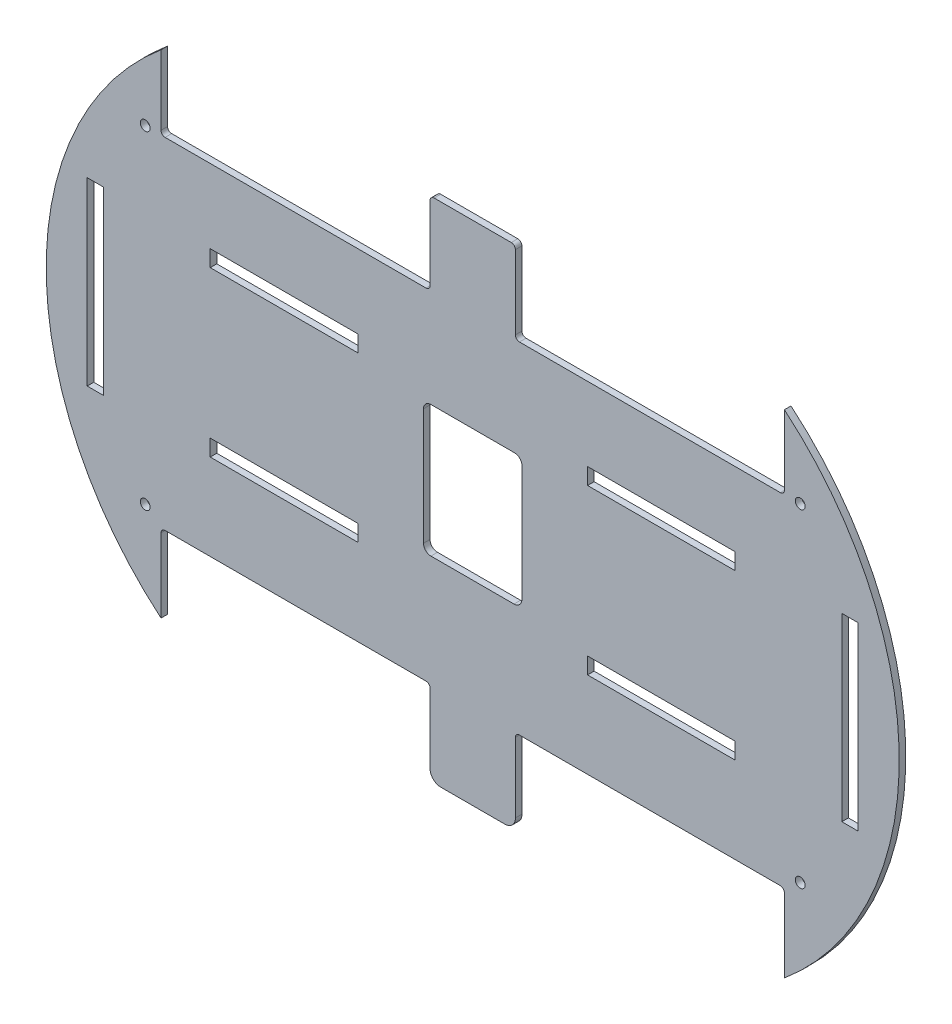
SolidWorks part; units mm, degrees
ref_plane "Front Plane" through (0, 0, 0) normal (0, 0, 1) x (1, 0, 0)
ref_plane "Top Plane" through (0, 0, 0) normal (0, 1, 0) x (1, 0, 0)
ref_plane "Right Plane" through (0, 0, 0) normal (1, 0, 0) x (0, 0, -1)
sketch "Szkic1" plane through (0, 0, 0) normal (0, 0, 1) x (1, 0, 0)
  line L0 (-139.7273, -79.5) -> (-120.189, -79.5)
  line L2 (0, 0) -> (-260, 0) construction
  line L3 (-223.75, 50) -> (-169.927, 50)
  line L4 (-143, 51.25) -> (-143, 73.75)
  line L5 (-225, 72.5) -> (-225, 51.25)
  line L6 (-141.75, 75) -> (-118.25, 75)
  line L7 (-223.75, -53.75) -> (-172.7811, -53.75)
  line L8 (-143, -55) -> (-143, -76.2376)
  line L10 (-130, 75) -> (-130, -75) construction
  line L12 (-225, -55) -> (-225, -77.5)
  line L16 (-157.927, 50) -> (-144.25, 50)
  line L20 (-157.573, -53.75) -> (-144.25, -53.75)
  line L29 (-117, 51.25) -> (-117, 73.75)
  line L38 (-102.427, -53.75) -> (-115.7693, -53.75)
  line L42 (-102.073, 50) -> (-115.75, 50)
  line L46 (-35, -55) -> (-35, -77.5)
  line L47 (-117, -54.9807) -> (-117, -76.25)
  line L48 (-36.25, -53.75) -> (-87.2189, -53.75)
  line L49 (-35, 72.5) -> (-35, 51.25)
  line L50 (-36.25, 50) -> (-90.073, 50)
  line L52 (-172.7811, -53.75) -> (-157.573, -53.75)
  line L53 (-169.927, 50) -> (-157.927, 50)
  line L54 (-102.073, 50) -> (-90.073, 50)
  line L55 (-87.2189, -53.75) -> (-102.427, -53.75)
  line L56 (-210, 27.5) -> (-165, 27.5)
  line L57 (-165, 27.5) -> (-165, 22.5)
  line L58 (-165, -27.5) -> (-210, -27.5)
  line L59 (-210, -27.5) -> (-210, -22.5)
  line L60 (-210, 22.5) -> (-165, 22.5)
  line L61 (-210, -22.5) -> (-165, -22.5)
  line L62 (-210, 22.5) -> (-210, 27.5)
  line L63 (-165, -22.5) -> (-165, -27.5)
  line L64 (-50, -22.5) -> (-95, -22.5)
  line L65 (-50, -27.5) -> (-50, -22.5)
  line L66 (-95, -27.5) -> (-50, -27.5)
  line L67 (-95, -22.5) -> (-95, -27.5)
  line L68 (-50, 22.5) -> (-50, 27.5)
  line L69 (-50, 22.5) -> (-95, 22.5)
  line L70 (-95, 27.5) -> (-95, 22.5)
  line L71 (-50, 27.5) -> (-95, 27.5)
  line L72 (-17.5, 27.5) -> (-12.5, 27.5)
  line L73 (-12.5, 27.5) -> (-12.5, -27.5)
  line L74 (-12.5, -27.5) -> (-17.5, -27.5)
  line L75 (-17.5, -27.5) -> (-17.5, 27.5)
  line L76 (-247.5, -27.5) -> (-242.5, -27.5)
  line L77 (-247.5, 27.5) -> (-247.5, -27.5)
  line L78 (-242.5, 27.5) -> (-247.5, 27.5)
  line L79 (-242.5, -27.5) -> (-242.5, 27.5)
  line L81 (-142.75, 20) -> (-117.25, 20)
  line L82 (-145, 17.75) -> (-145, -17.75)
  line L83 (-142.75, -20) -> (-117.427, -20)
  line L84 (-115, 17.75) -> (-115, -17.573)
  arc A0 (-225, -77.5) -> (-225, 72.5) centre (-162.1429, -2.5) cw
  circle A1 centre (-229.8183, 50.1102) radius 1.5
  circle A2 centre (-229.8183, -49.8898) radius 1.5
  circle A3 centre (-30.1817, -49.8898) radius 1.5
  circle A4 centre (-30.1817, 50.1102) radius 1.5
  arc A5 (-35, -77.5) -> (-35, 72.5) centre (-97.8571, -2.5) ccw
  arc A6 (-117, 51.25) -> (-115.75, 50) centre (-115.75, 51.25) ccw
  arc A7 (-36.25, 50) -> (-35, 51.25) centre (-36.25, 51.25) ccw
  arc A8 (-117, 73.75) -> (-118.25, 75) centre (-118.25, 73.75) ccw
  arc A9 (-141.75, 75) -> (-143, 73.75) centre (-141.75, 73.75) ccw
  arc A10 (-144.25, 50) -> (-143, 51.25) centre (-144.25, 51.25) ccw
  arc A11 (-143, -55) -> (-144.25, -53.75) centre (-144.25, -55) ccw
  arc A14 (-115.7693, -53.75) -> (-117, -54.9807) centre (-115.7693, -54.9807) ccw
  arc A15 (-35, -55) -> (-36.25, -53.75) centre (-36.25, -55) ccw
  arc A16 (-223.75, -53.75) -> (-225, -55) centre (-223.75, -55) ccw
  arc A17 (-225, 51.25) -> (-223.75, 50) centre (-223.75, 51.25) ccw
  arc A21 (-142.75, 20) -> (-145, 17.75) centre (-142.75, 17.75) ccw
  arc A22 (-115, 17.75) -> (-117.25, 20) centre (-117.25, 17.75) ccw
  arc A23 (-117.427, -20) -> (-115, -17.573) centre (-117.427, -17.573) ccw
  arc A24 (-145, -17.75) -> (-142.75, -20) centre (-142.75, -17.75) ccw
  arc A27 (-143, -76.2376) -> (-139.7273, -79.5) centre (-139.7376, -76.2376) ccw
  arc A28 (-120.189, -79.5) -> (-117, -76.25) centre (-120.189, -76.3104) ccw
  point P54 (0, -2.5)
  dimension "D12" = 27.5
  dimension "D19" = 97.8571
  dimension "D24" = 3
  dimension "D25" = 3
  dimension "D9" = 2.5
  dimension "D26" = 2.5
  dimension "D27" = 2.5
  dimension "D22" = 82
  dimension "D14" = 82
  dimension "D23" = 20
  dimension "D29" = 4.5
  dimension "D30" = 82
  dimension "D2" = 260
  dimension "D3" = 22.5
  dimension "D4" = 150
  dimension "D5" = 22.5
  dimension "D6" = 45
  dimension "D7" = 50
  dimension "D8" = 5
  dimension "D10" = 59.5
  dimension "D11" = 5
  dimension "D13" = 27.5
  dimension "D15" = 22.5
  dimension "D16" = 5
  dimension "D17" = 12.5
  dimension "D18" = 32.5
  dimension "D20" = 12.5
  dimension "D21" = 25
  dimension "D28" = 15
  dimension "D31" = 97.5
  dimension "D32" = 97.5
  dimension "D34" = 82
extrude "Dodanie-wyciągnięcie3" add sketch "Szkic1" along normal blind 2
